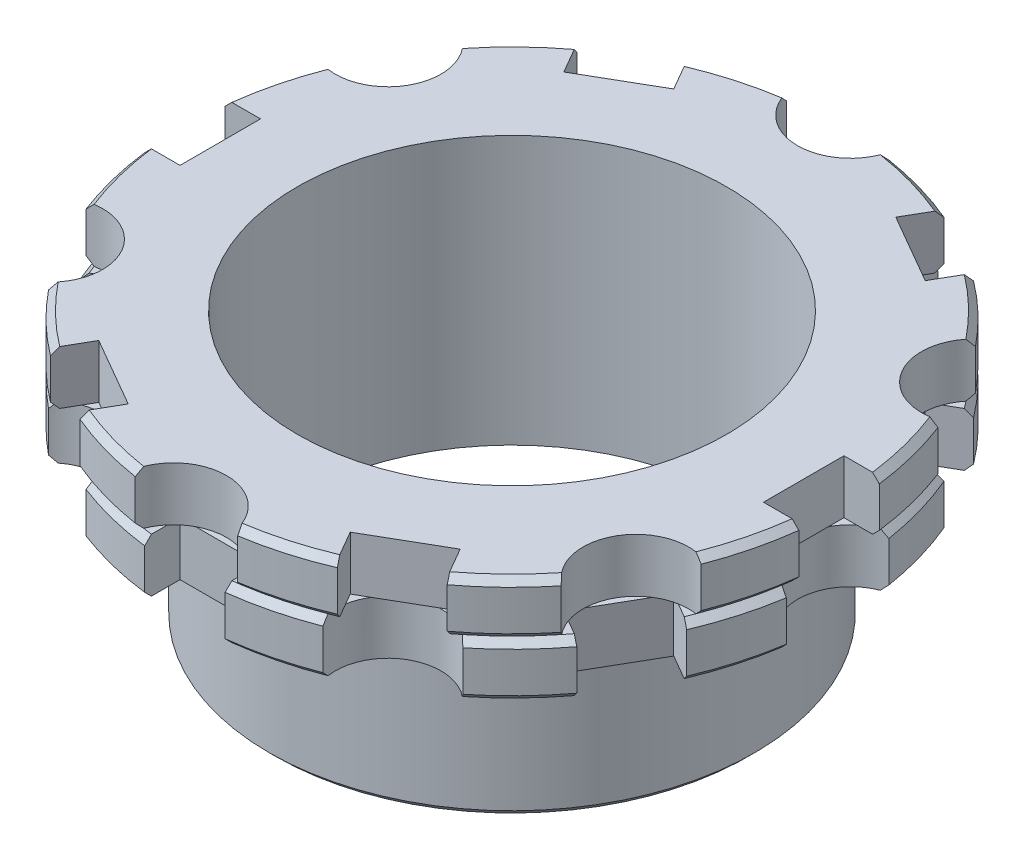
SolidWorks part; units mm, degrees
ref_plane "Front Plane" through (0, 0, 0) normal (0, 0, 1) x (1, 0, 0)
ref_plane "Top Plane" through (0, 0, 0) normal (0, 1, 0) x (1, 0, 0)
ref_plane "Right Plane" through (0, 0, 0) normal (1, 0, 0) x (0, 0, -1)
sketch "Sketch1" plane through (0, 0, 0) normal (1, 0, 0) x (0, 0, -1)
  line L0 (0, 0) -> (0, -128.8795) construction
  line L1 (16, -67) -> (17.6, -67)
  line L2 (18.1, -66.5) -> (18.1, -55.4)
  line L3 (18.5, -55) -> (24.07, -55)
  line L4 (24.57, -54.5) -> (24.57, -51.5)
  line L5 (24.07, -47) -> (16, -47)
  line L6 (24.07, -55) -> (24.57, -54.5)
  line L7 (24.57, -47.5) -> (24.07, -47)
  line L8 (17.6, -67) -> (18.1, -66.5)
  line L9 (24.57, -51) -> (24.07, -51) construction
  line L10 (24.07, -51) -> (24.57, -51.5)
  line L11 (24.07, -51) -> (24.57, -50.5)
  line L12 (24.57, -50.5) -> (24.57, -47.5)
  line L13 (0, -47) -> (0, -67) construction
  line L14 (16, -47) -> (16, -67)
  line L15 (16, -47) -> (0, -47) construction
  line L16 (0, -67) -> (16, -67) construction
  arc A0 (18.1, -55.4) -> (18.5, -55) centre (18.5, -55.4) cw
  point P4 (18.1, -67)
  point P5 (24.57, -55)
  point P8 (24.57, -47)
  dimension "D6" = 0.4
  dimension "D1" = 47
  dimension "D2" = 24.57
  dimension "D3" = 8
  dimension "D4" = 18.1
  dimension "D5" = 20
  dimension "D7" = 0.5
  dimension "D8" = 1
  dimension "D9" = 4
  dimension "D13" = 32
revolve "Revolve1" add sketch "Sketch1" angle 360 about L0
sketch "Sketch2" plane through (0, -47, 0) normal (0, 1, 0) x (1, 0, 0)
  line L0 (0, 0) -> (0, 29.3434) construction
  line L1 (0, 0) -> (30.1418, 0) construction
  line L2 (0, 0) -> (14.375, 24.8982) construction
  line L4 (11.7769, 26.3982) -> (8.2769, 20.3361)
  line L5 (8.2769, 20.3361) -> (13.4731, 17.3361)
  line L6 (13.4731, 17.3361) -> (16.9731, 23.3982)
  line L7 (16.9731, 23.3982) -> (11.7769, 26.3982)
  line L9 (28.75, 3) -> (21.75, 3)
  line L10 (21.75, 3) -> (21.75, -3)
  line L11 (21.75, -3) -> (28.75, -3)
  line L12 (28.75, -3) -> (28.75, 3)
  line L13 (16.9731, -23.3982) -> (13.4731, -17.3361)
  line L14 (13.4731, -17.3361) -> (8.2769, -20.3361)
  line L15 (8.2769, -20.3361) -> (11.7769, -26.3982)
  line L16 (11.7769, -26.3982) -> (16.9731, -23.3982)
  line L17 (-11.7769, -26.3982) -> (-8.2769, -20.3361)
  line L18 (-8.2769, -20.3361) -> (-13.4731, -17.3361)
  line L19 (-13.4731, -17.3361) -> (-16.9731, -23.3982)
  line L20 (-16.9731, -23.3982) -> (-11.7769, -26.3982)
  line L21 (-28.75, -3) -> (-21.75, -3)
  line L22 (-21.75, -3) -> (-21.75, 3)
  line L23 (-21.75, 3) -> (-28.75, 3)
  line L24 (-28.75, 3) -> (-28.75, -3)
  line L25 (-16.9731, 23.3982) -> (-13.4731, 17.3361)
  line L26 (-13.4731, 17.3361) -> (-8.2769, 20.3361)
  line L27 (-8.2769, 20.3361) -> (-11.7769, 26.3982)
  line L28 (-11.7769, 26.3982) -> (-16.9731, 23.3982)
  circle A2 centre (0, 25.23) radius 3.94
  circle A3 centre (21.8498, 12.615) radius 3.94
  circle A4 centre (21.8498, -12.615) radius 3.94
  circle A5 centre (0, -25.23) radius 3.94
  circle A6 centre (-21.8498, -12.615) radius 3.94
  circle A7 centre (-21.8498, 12.615) radius 3.94
  dimension "D1" = 7.88
  dimension "D2" = 25.23
  dimension "D3" = 30
  dimension "D4" = 6
  dimension "D5" = 21.75
  dimension "D6" = 7
  dimension "D8" = 21.8498
  dimension "D9" = 12.615
  dimension "D7" = 6
extrude "Cut-Extrude1" cut sketch "Sketch2" against normal blind 4
sketch "Sketch3" plane through (0, -51, 0) normal (0, 1, 0) x (1, 0, 0)
  line L0 (0, 0) -> (0, 28.4734) construction
  line L1 (0, 0) -> (37.507, 0) construction
  line L2 (-3, 28.75) -> (-3, 21.75)
  line L3 (-3, 21.75) -> (3, 21.75)
  line L4 (3, 21.75) -> (3, 28.75)
  line L5 (3, 28.75) -> (-3, 28.75)
  line L6 (0, 0) -> (12.615, 21.8498) construction
  line L7 (23.3982, 16.9731) -> (17.3361, 13.4731)
  line L8 (17.3361, 13.4731) -> (20.3361, 8.2769)
  line L9 (20.3361, 8.2769) -> (26.3982, 11.7769)
  line L10 (26.3982, 11.7769) -> (23.3982, 16.9731)
  line L11 (26.3982, -11.7769) -> (20.3361, -8.2769)
  line L12 (20.3361, -8.2769) -> (17.3361, -13.4731)
  line L13 (17.3361, -13.4731) -> (23.3982, -16.9731)
  line L14 (23.3982, -16.9731) -> (26.3982, -11.7769)
  line L15 (3, -28.75) -> (3, -21.75)
  line L16 (3, -21.75) -> (-3, -21.75)
  line L17 (-3, -21.75) -> (-3, -28.75)
  line L18 (-3, -28.75) -> (3, -28.75)
  line L19 (-23.3982, -16.9731) -> (-17.3361, -13.4731)
  line L20 (-17.3361, -13.4731) -> (-20.3361, -8.2769)
  line L21 (-20.3361, -8.2769) -> (-26.3982, -11.7769)
  line L22 (-26.3982, -11.7769) -> (-23.3982, -16.9731)
  line L23 (-26.3982, 11.7769) -> (-20.3361, 8.2769)
  line L24 (-20.3361, 8.2769) -> (-17.3361, 13.4731)
  line L25 (-17.3361, 13.4731) -> (-23.3982, 16.9731)
  line L26 (-23.3982, 16.9731) -> (-26.3982, 11.7769)
  circle A0 centre (12.615, 21.8498) radius 3.94
  circle A1 centre (25.23, 0) radius 3.94
  circle A2 centre (12.615, -21.8498) radius 3.94
  circle A3 centre (-12.615, -21.8498) radius 3.94
  circle A4 centre (-25.23, 0) radius 3.94
  circle A5 centre (-12.615, 21.8498) radius 3.94
  dimension "D5" = 7.88
  dimension "D1" = 6
  dimension "D2" = 21.75
  dimension "D3" = 7
  dimension "D4" = 30
  dimension "D6" = 25.23
  dimension "D8" = 25.23
  dimension "D9" = 20.3361
  dimension "D7" = 6
extrude "Cut-Extrude2" cut sketch "Sketch3" against normal blind 4
sketch "Sketch4" plane through (0, -55, 0) normal (0, -1, 0) x (1, 0, 0)
  circle A0 centre (0, 0) radius 18.5
